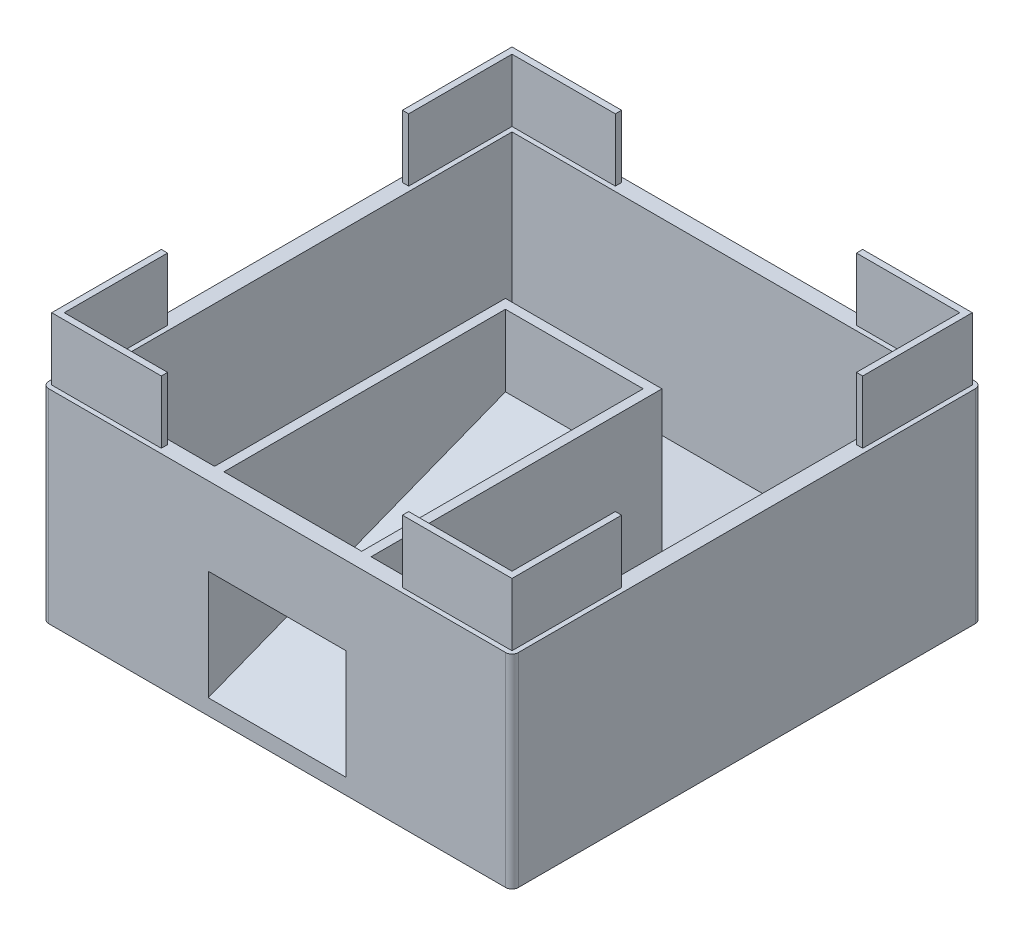
SolidWorks part; units mm, degrees
ref_plane "Front Plane" through (0, 0, 0) normal (0, 0, 1) x (1, 0, 0)
ref_plane "Top Plane" through (0, 0, 0) normal (0, 1, 0) x (1, 0, 0)
ref_plane "Right Plane" through (0, 0, 0) normal (1, 0, 0) x (0, 0, -1)
sketch "Sketch1" plane through (0, 0, 0) normal (0, 1, 0) x (1, 0, 0)
  line L1 (0, 0) -> (150, 0)
  line L2 (0, 0) -> (0, 150)
  line L3 (0, 150) -> (150, 150)
  line L4 (150, 0) -> (150, 150)
  dimension "D1" = 150
  dimension "D2" = 150
extrude "Boss-Extrude1" add sketch "Sketch1" along normal blind 65
shell "Shell1" thickness 5
fillet "Fillet1" radius 2 4 edges at (0, 32.5, -150) (150, 32.5, -150) (150, 32.5, 0) (0, 32.5, 0)
sketch "Sketch2" plane through (0, 65, 0) normal (0, 1, 0) x (1, 0, 0)
  line L0 (1.5, 148.5) -> (36.5, 148.5)
  line L1 (36.5, 148.5) -> (36.5, 146.5)
  line L2 (36.5, 146.5) -> (3.5, 146.5)
  line L3 (3.5, 146.5) -> (3.5, 113.5)
  line L4 (3.5, 113.5) -> (1.5, 113.5)
  line L5 (1.5, 113.5) -> (1.5, 148.5)
  line L6 (1.5, 148.5) -> (36.5, 148.5)
  line L7 (75, 186.357) -> (75, 26.357) construction
  line L8 (-6.7075, 75) -> (153.2925, 75) construction
  line L9 (148.5, 113.5) -> (148.5, 148.5)
  line L10 (146.5, 113.5) -> (148.5, 113.5)
  line L11 (36.5, 148.5) -> (36.5, 146.5)
  line L12 (36.5, 146.5) -> (3.5, 146.5)
  line L13 (3.5, 146.5) -> (3.5, 113.5)
  line L14 (3.5, 113.5) -> (1.5, 113.5)
  line L15 (1.5, 113.5) -> (1.5, 148.5)
  line L16 (146.5, 146.5) -> (146.5, 113.5)
  line L17 (113.5, 146.5) -> (146.5, 146.5)
  line L18 (113.5, 148.5) -> (113.5, 146.5)
  line L19 (148.5, 148.5) -> (113.5, 148.5)
  line L20 (148.5, 113.5) -> (148.5, 148.5)
  line L21 (146.5, 113.5) -> (148.5, 113.5)
  line L22 (146.5, 146.5) -> (146.5, 113.5)
  line L23 (113.5, 146.5) -> (146.5, 146.5)
  line L24 (113.5, 148.5) -> (113.5, 146.5)
  line L25 (148.5, 148.5) -> (113.5, 148.5)
  line L26 (148.5, 1.5) -> (113.5, 1.5)
  line L27 (113.5, 1.5) -> (113.5, 3.5)
  line L28 (113.5, 3.5) -> (146.5, 3.5)
  line L29 (146.5, 3.5) -> (146.5, 36.5)
  line L30 (146.5, 36.5) -> (148.5, 36.5)
  line L31 (148.5, 36.5) -> (148.5, 1.5)
  line L32 (148.5, 1.5) -> (113.5, 1.5)
  line L33 (113.5, 1.5) -> (113.5, 3.5)
  line L34 (113.5, 3.5) -> (146.5, 3.5)
  line L35 (146.5, 3.5) -> (146.5, 36.5)
  line L36 (1.5, 36.5) -> (1.5, 1.5)
  line L37 (3.5, 36.5) -> (1.5, 36.5)
  line L38 (3.5, 3.5) -> (3.5, 36.5)
  line L39 (36.5, 3.5) -> (3.5, 3.5)
  line L40 (36.5, 1.5) -> (36.5, 3.5)
  line L41 (146.5, 36.5) -> (148.5, 36.5)
  line L42 (148.5, 36.5) -> (148.5, 1.5)
  line L43 (1.5, 1.5) -> (36.5, 1.5)
  line L44 (1.5, 36.5) -> (1.5, 1.5)
  line L45 (3.5, 36.5) -> (1.5, 36.5)
  line L46 (3.5, 3.5) -> (3.5, 36.5)
  line L47 (36.5, 3.5) -> (3.5, 3.5)
  line L48 (36.5, 1.5) -> (36.5, 3.5)
  line L49 (1.5, 1.5) -> (36.5, 1.5)
  line L50 (148, 150) -> (2, 150) construction
  line L51 (0, 148) -> (0, 2) construction
  line L52 (2, 0) -> (148, 0) construction
  line L53 (150, 2) -> (150, 148) construction
  dimension "D1" = 2
  dimension "D2" = 35
  dimension "D3" = 35
  dimension "D4" = 2
  dimension "D5" = 1.5
  dimension "D6" = 1.5
  dimension "D7" = 1.5
  dimension "D8" = 1.5
extrude "Boss-Extrude2" add sketch "Sketch2" along normal blind 20 contours L5 L4 L3 L2 L1 L0 | L9 L19 L18 L17 L16 L10 | L31 L30 L29 L28 L27 L26 | L36 L43 L40 L39 L38 L37
sketch "Sketch3" plane through (0, 0, 0) normal (0, 0, 1) x (1, 0, 0)
  line L0 (0, 0) -> (0, 65) construction
  line L1 (53, 5) -> (97, 5)
  line L2 (53, 5) -> (53, 40)
  line L3 (53, 40) -> (97, 40)
  line L4 (97, 5) -> (97, 40)
  line L5 (2, 0) -> (148, 0) construction
  dimension "D1" = 53
  dimension "D2" = 44
  dimension "D3" = 35
  dimension "D4" = 5
extrude "Cut-Extrude1" cut sketch "Sketch3" against normal up to next
sketch "Sketch4" plane through (0, 5, 0) normal (0, 1, 0) x (1, 0, 0)
  line L0 (53, 5) -> (53, 94.9)
  line L1 (5, 5) -> (53, 5) construction
  line L2 (53, 94.9) -> (97, 94.9)
  line L3 (97, 94.9) -> (97, 5)
  line L4 (97, 5) -> (145, 5) construction
  line L5 (97, 5) -> (100, 5)
  line L6 (100, 5) -> (100, 97.9)
  line L7 (100, 97.9) -> (50, 97.9)
  line L8 (50, 97.9) -> (50, 5)
  line L9 (50, 5) -> (53, 5)
  dimension "D1" = 92.9
  dimension "D2" = 3
  dimension "D3" = 3
  dimension "D6" = 3
extrude "Boss-Extrude3" add sketch "Sketch4" along normal blind 60
ref_plane "Plane1" through (75, 0, 0) normal (1, 0, 0) x (0, 0, -1)
sketch "Sketch7" plane through (75, 0, 0) normal (1, 0, 0) x (0, 0, -1)
  line L0 (94.9, 42.1586) -> (0, 5)
  line L1 (94.9, 65) -> (94.9, 5) construction
  line L8 (5, 40) -> (0, 40)
  line L9 (0, 40) -> (0, 5)
  line L10 (0, 5) -> (94.9, 5)
  line L11 (94.9, 5) -> (94.9, 65)
  line L12 (94.9, 65) -> (5, 65)
  line L13 (5, 65) -> (5, 40)
  line L16 (0, 5) -> (94.9, 5)
  line L17 (94.9, 5) -> (94.9, 42.1586)
  dimension "D1" = 0
extrude "Boss-Extrude4" add sketch "Sketch7" along normal up to next and the other way up to next
